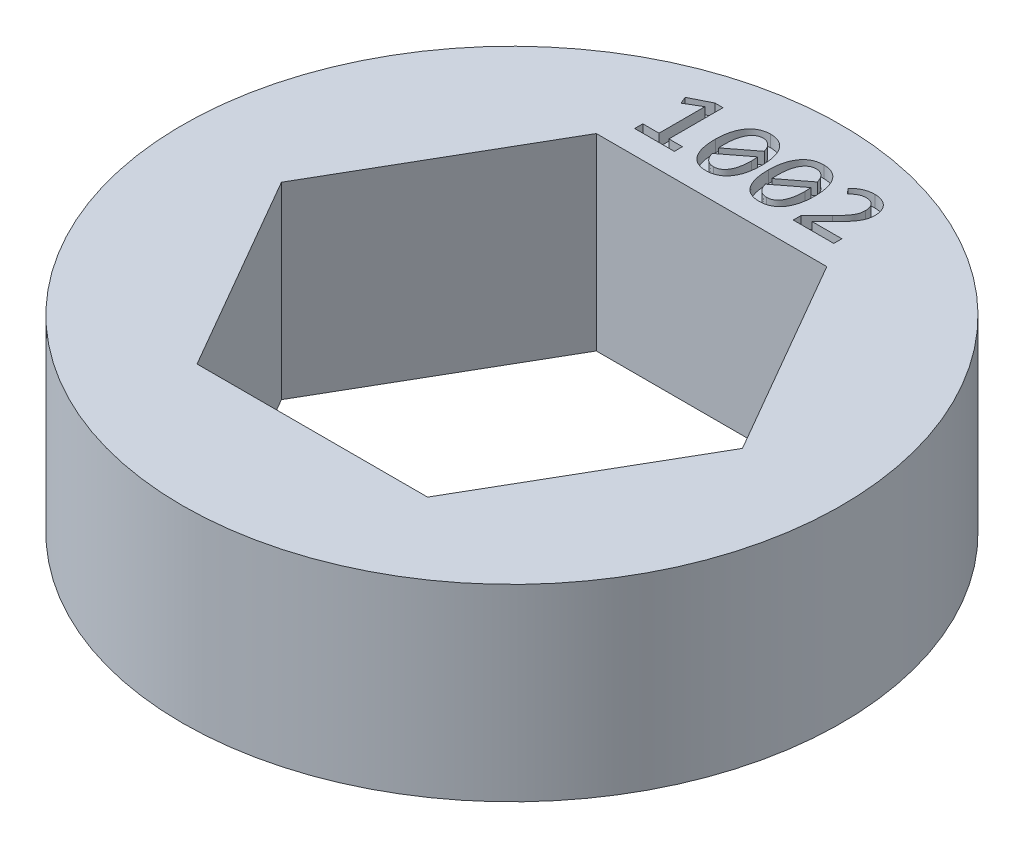
SolidWorks part; units mm, degrees
material "Nylon 101"
ref_plane "Front Plane" through (0, 0, 0) normal (0, 0, 1) x (1, 0, 0)
ref_plane "Top Plane" through (0, 0, 0) normal (0, 1, 0) x (1, 0, 0)
ref_plane "Right Plane" through (0, 0, 0) normal (1, 0, 0) x (0, 0, -1)
sketch "Sketch1" plane through (0, 0, 0) normal (0, 1, 0) x (1, 0, 0)
  line L1 (7.7723, 0) -> (3.8861, 6.731)
  line L2 (3.8861, 6.731) -> (-3.8861, 6.731)
  line L3 (-3.8861, 6.731) -> (-7.7723, 0)
  line L4 (-7.7723, 0) -> (-3.8861, -6.731)
  line L5 (-3.8861, -6.731) -> (3.8861, -6.731)
  line L6 (3.8861, -6.731) -> (7.7723, 0)
  circle A0 centre (0, 0) radius 6.731 construction
  circle A1 centre (0, 0) radius 11.1125
  dimension "D1" = 13.462
  dimension "D2" = 22.225
extrude "Boss-Extrude1" add sketch "Sketch1" along normal blind 6.35
sketch "Sketch2" plane through (0, 6.35, 0) normal (0, 1, 0) x (1, 0, 0)
  line L0 (-4.2615, 7.5247) -> (4.1119, 7.5247) construction
  line L1 (3.8861, 6.731) -> (-3.8861, 6.731) construction
  text T0 "1002\r\n" font "Consolas" height in points 8
  dimension "D1" = 0.7937
extrude "Cut-Extrude1" cut sketch "Sketch2" against normal blind 0.4
